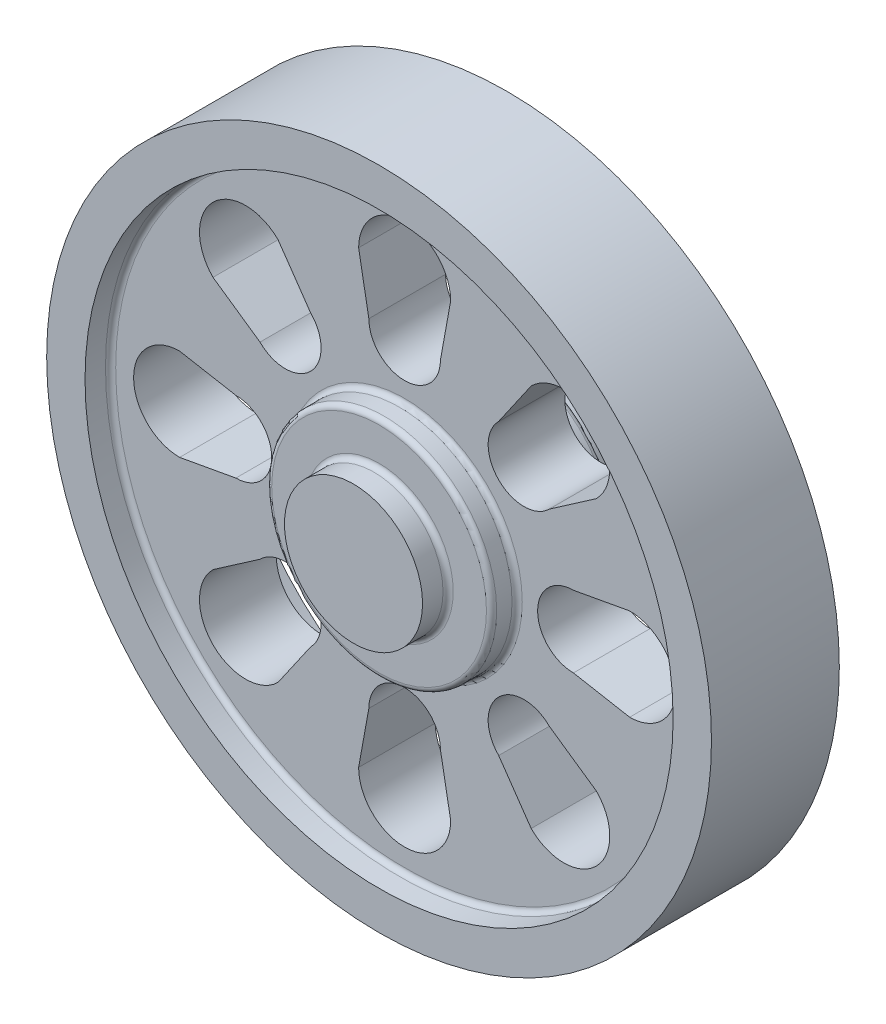
SolidWorks part; units mm, degrees
ref_plane "Front Plane" through (0, 0, 0) normal (0, 0, 1) x (1, 0, 0)
ref_plane "Top Plane" through (0, 0, 0) normal (0, 1, 0) x (1, 0, 0)
ref_plane "Right Plane" through (0, 0, 0) normal (1, 0, 0) x (0, 0, -1)
sketch "Sketch1" plane through (0, 0, 0) normal (0, 0, 1) x (1, 0, 0)
  circle A0 centre (0, 0) radius 6.5
  dimension "D1" = 13
extrude "Boss-Extrude1" add sketch "Sketch1" along normal blind 2.5
sketch "Sketch2" plane through (0, 0, 2.5) normal (0, 0, 1) x (1, 0, 0)
  circle A0 centre (0, 0) radius 5.75
  circle A1 centre (0, 0) radius 6.5
  circle A2 centre (0, 0) radius 6.5
  dimension "D1" = 0
  dimension "D2" = 0.75
extrude "Cut-Extrude1" cut sketch "Sketch2" against normal blind 0.5 separate body contours A0
sketch "Sketch3" plane through (0, 0, 0) normal (0, 0, -1) x (-1, 0, 0)
  circle A0 centre (0, 0) radius 5.75
  circle A1 centre (0, 0) radius 6.5
  circle A2 centre (0, 0) radius 6.5
  dimension "D1" = 0
  dimension "D2" = 0.75
extrude "Cut-Extrude2" cut sketch "Sketch3" against normal blind 0.5 separate body contours A0
sketch "Sketch4" plane through (0, 0, 2) normal (0, 0, 1) x (1, 0, 0)
  circle A0 centre (0, 0) radius 2.2
  circle A1 centre (0, 0) radius 5.75
  circle A2 centre (0, 0) radius 5.75
  dimension "D2" = 4.4
  dimension "D1" = 0
extrude "Boss-Extrude2" add sketch "Sketch4" along normal blind 0.5 and the other way blind 2 contours A0
sketch "Sketch5" plane through (0, 0, 2) normal (0, 0, 1) x (1, 0, 0)
  line L0 (0, 5.75) -> (0, -5.75) construction
  line L2 (-0.9, 4.4) -> (-0.7, 3.3)
  line L3 (0.9, 4.4) -> (0.7, 3.3)
  line L4 (3.7477, 2.4749) -> (2.8284, 1.8385)
  line L5 (2.4749, 3.7477) -> (1.8385, 2.8284)
  line L6 (4.4, -0.9) -> (3.3, -0.7)
  line L7 (4.4, 0.9) -> (3.3, 0.7)
  line L8 (2.4749, -3.7477) -> (1.8385, -2.8284)
  line L9 (3.7477, -2.4749) -> (2.8284, -1.8385)
  line L10 (-0.9, -4.4) -> (-0.7, -3.3)
  line L11 (0.9, -4.4) -> (0.7, -3.3)
  line L12 (-3.7477, -2.4749) -> (-2.8284, -1.8385)
  line L13 (-2.4749, -3.7477) -> (-1.8385, -2.8284)
  line L14 (-4.4, 0.9) -> (-3.3, 0.7)
  line L15 (-4.4, -0.9) -> (-3.3, -0.7)
  line L16 (-2.4749, 3.7477) -> (-1.8385, 2.8284)
  line L17 (-3.7477, 2.4749) -> (-2.8284, 1.8385)
  arc A0 (0.9, 4.4) -> (-0.9, 4.4) centre (0, 4.4) ccw
  arc A3 (-0.7, 3.3) -> (0.7, 3.3) centre (0, 3.3) ccw
  arc A4 (1.8385, 2.8284) -> (2.8284, 1.8385) centre (2.3335, 2.3335) ccw
  arc A5 (3.7477, 2.4749) -> (2.4749, 3.7477) centre (3.1113, 3.1113) ccw
  arc A6 (3.3, 0.7) -> (3.3, -0.7) centre (3.3, 0) ccw
  arc A7 (4.4, -0.9) -> (4.4, 0.9) centre (4.4, 0) ccw
  arc A8 (2.8284, -1.8385) -> (1.8385, -2.8284) centre (2.3335, -2.3335) ccw
  arc A9 (2.4749, -3.7477) -> (3.7477, -2.4749) centre (3.1113, -3.1113) ccw
  arc A10 (0.7, -3.3) -> (-0.7, -3.3) centre (0, -3.3) ccw
  arc A11 (-0.9, -4.4) -> (0.9, -4.4) centre (0, -4.4) ccw
  arc A12 (-1.8385, -2.8284) -> (-2.8284, -1.8385) centre (-2.3335, -2.3335) ccw
  arc A13 (-3.7477, -2.4749) -> (-2.4749, -3.7477) centre (-3.1113, -3.1113) ccw
  arc A14 (-3.3, -0.7) -> (-3.3, 0.7) centre (-3.3, 0) ccw
  arc A15 (-4.4, 0.9) -> (-4.4, -0.9) centre (-4.4, 0) ccw
  arc A16 (-2.8284, 1.8385) -> (-1.8385, 2.8284) centre (-2.3335, 2.3335) ccw
  arc A17 (-2.4749, 3.7477) -> (-3.7477, 2.4749) centre (-3.1113, 3.1113) ccw
  point P9 (0, 5.3)
  point P10 (0, 2.6)
  point P58 (0, 0)
  dimension "D3" = 1.4
  dimension "D4" = 1.8
  dimension "D5" = 2.7
  dimension "D6" = 8
extrude "Cut-Extrude3" cut sketch "Sketch5" against normal through all separate body
sketch "Sketch6" plane through (0, 0, 2.5) normal (0, 0, 1) x (1, 0, 0)
  circle A0 centre (0, 0) radius 1.35
  circle A1 centre (0, 0) radius 2.2
  circle A2 centre (0, 0) radius 2.2
  dimension "D2" = 2.7
  dimension "D1" = 0
extrude "Boss-Extrude3" add sketch "Sketch6" along normal blind 0.5 contours A0
sketch "Sketch7" plane through (0, 0, 3) normal (0, 0, 1) x (1, 0, 0)
  circle A1 centre (0, 0) radius 1.35
  circle A2 centre (0, 0) radius 1.35
  dimension "D1" = 0
extrude "Boss-Extrude4" add sketch "Sketch7" against normal blind 2.5 from surface at -3 contours A2 starting at face at (2.2, 0, 0)
fillet "Fillet5" radius 0.1 4 edges at (5.75, 0, 2) (1.35, 0, 2.5) (2.2, 0, 2.5) (2.2, 0, 2)
fillet "Fillet6" radius 0.1 4 edges at (-5.75, 0, 0.5) (-2.2, 0, 0.5) (2.2, 0, 0) (1.35, 0, 0)
